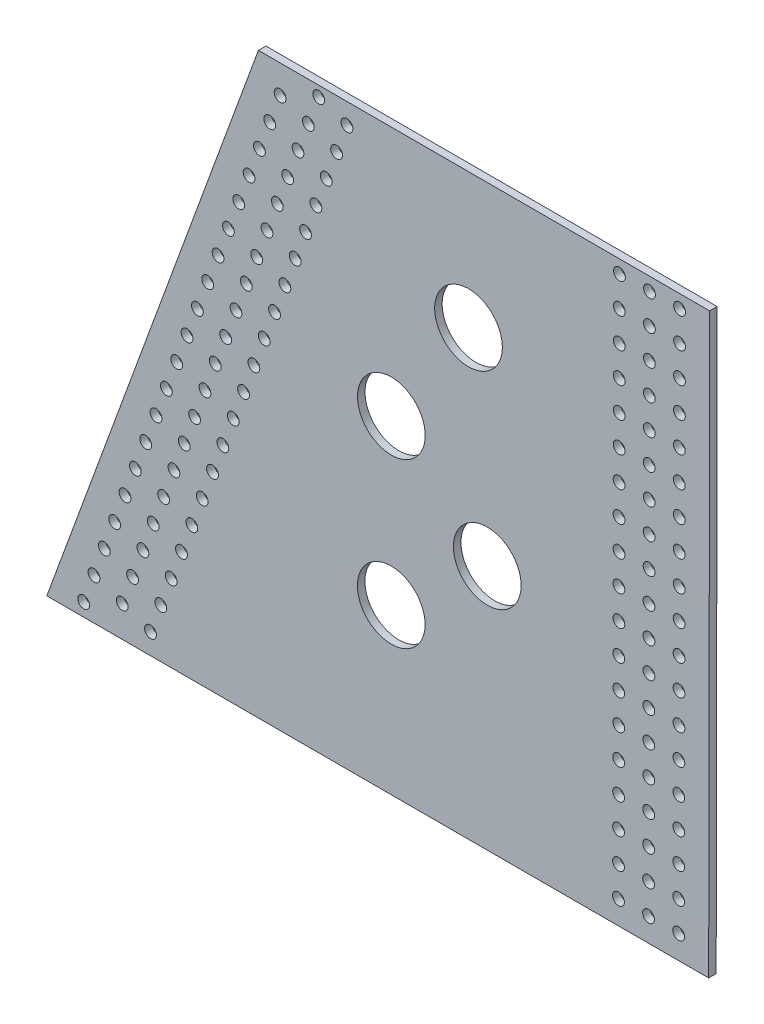
SolidWorks part; units mm, degrees
ref_plane "Front Plane" through (0, 0, 0) normal (0, 0, 1) x (1, 0, 0)
ref_plane "Top Plane" through (0, 0, 0) normal (0, 1, 0) x (1, 0, 0)
ref_plane "Right Plane" through (0, 0, 0) normal (1, 0, 0) x (0, 0, -1)
sketch "Sketch4" plane through (0, 0, 0) normal (0, 0, 1) x (1, 0, 0)
  line B0 (93.7764, 244.0959) -> (284.2764, 244.0959)
  line B1 (284.2764, 244.0959) -> (283.8532, 0)
  line B2 (283.8532, 0) -> (4.4532, 0)
  line B3 (4.4532, 0) -> (93.7764, 244.0959)
  circle B4 centre (182.4682, 187.0319) radius 14.2875
  circle B5 centre (149.9008, 138.4688) radius 14.2875
  circle B6 centre (134.0055, 158.4355) radius 2.4892
  circle B7 centre (165.6949, 118.7313) radius 2.4892
  circle B8 centre (190.3928, 103.8494) radius 14.2875
  circle B9 centre (149.8584, 69.3292) radius 14.2875
  circle B10 centre (197.3682, 18.7438) radius 2.4892
  circle B11 centre (115.0722, 40.7409) radius 9.525
  circle B12 centre (184.6682, 40.7409) radius 9.525
  circle B13 centre (210.0682, 40.7409) radius 2.4892
  circle B14 centre (171.9682, 18.7438) radius 2.4892
  circle B15 centre (159.2682, 40.7409) radius 2.4892
  circle B16 centre (171.9682, 62.7379) radius 2.4892
  circle B17 centre (197.3682, 62.7379) radius 2.4892
  circle B18 centre (140.4722, 40.7409) radius 2.4892
  circle B19 centre (127.7722, 18.7438) radius 2.4892
  circle B20 centre (102.3722, 18.7438) radius 2.4892
  circle B21 centre (89.6722, 40.7409) radius 2.4892
  circle B22 centre (102.3722, 62.7379) radius 2.4892
  circle B23 centre (127.7722, 62.7379) radius 2.4892
sketch_block_instance "Block-Gearbox_Plate1-2"
sketch_block "Block-Gearbox_Plate1" parameters "D3"=28.575, "D4"=4.9784, "D5"=4.9784, "D6"=28.575, "D7"=28.575, "D8"=28.575, "D9"=19.05, "D10"=19.05, "D11"=4.9784, "D14"=4.9784, "D1"=190.5, "D2"=279.4, "D12"=25.4, "D13"=25.4, "D15"=25.4
extrude "Boss-Extrude2" add sketch "Sketch4" along normal blind 3.175 separate body
sketch "Sketch11" plane through (0, 0, 3.175) normal (0, 0, 1) x (1, 0, 0)
  line L0 (231.6101, -832.4231) -> (318.2903, 49167.5018) construction
  line L6 (283.8532, 0) -> (284.2764, 244.0959) construction
  line L7 (284.2764, 244.0959) -> (93.7764, 244.0959) construction
  line L8 (271.5667, 238.5079) -> (258.8667, 238.5079) construction
  line L9 (271.5667, 238.5079) -> (271.5447, 225.8079) construction
  line L10 (4.4532, 0) -> (283.8532, 0) construction
  line L11 (135.8908, 211.3577) -> (-17046.5435, -46743.5564) construction
  line L12 (93.7764, 244.0959) -> (4.4532, 0) construction
  line L13 (93.7764, 244.0959) -> (47048.6904, -16938.3384) construction
  line L14 (102.9315, 232.1579) -> (114.858, 227.7936) construction
  line L15 (102.9315, 232.1579) -> (98.5671, 220.2313) construction
  line L16 (114.858, 227.7936) -> (119.2224, 239.7201) construction
  circle A0 centre (271.5667, 238.5079) radius 2.4892
  circle A1 centre (258.8667, 238.5079) radius 2.4892
  circle A2 centre (246.1667, 238.5079) radius 2.4892
  circle A3 centre (258.8447, 225.8079) radius 2.4892
  circle A4 centre (246.1447, 225.8079) radius 2.4892
  circle A5 centre (258.8227, 213.1079) radius 2.4892
  circle A6 centre (246.1227, 213.1079) radius 2.4892
  circle A7 centre (258.8006, 200.4079) radius 2.4892
  circle A8 centre (246.1006, 200.4079) radius 2.4892
  circle A9 centre (258.7786, 187.708) radius 2.4892
  circle A10 centre (246.0786, 187.708) radius 2.4892
  circle A11 centre (258.7566, 175.008) radius 2.4892
  circle A12 centre (246.0566, 175.008) radius 2.4892
  circle A13 centre (258.7346, 162.308) radius 2.4892
  circle A14 centre (246.0346, 162.308) radius 2.4892
  circle A15 centre (258.7126, 149.608) radius 2.4892
  circle A16 centre (246.0126, 149.608) radius 2.4892
  circle A17 centre (258.6906, 136.908) radius 2.4892
  circle A18 centre (245.9906, 136.908) radius 2.4892
  circle A19 centre (258.6685, 124.2081) radius 2.4892
  circle A20 centre (245.9685, 124.2081) radius 2.4892
  circle A21 centre (258.6465, 111.5081) radius 2.4892
  circle A22 centre (245.9465, 111.5081) radius 2.4892
  circle A23 centre (258.6245, 98.8081) radius 2.4892
  circle A24 centre (245.9245, 98.8081) radius 2.4892
  circle A25 centre (258.6025, 86.1081) radius 2.4892
  circle A26 centre (245.9025, 86.1081) radius 2.4892
  circle A27 centre (258.5805, 73.4081) radius 2.4892
  circle A28 centre (245.8805, 73.4081) radius 2.4892
  circle A29 centre (258.5585, 60.7082) radius 2.4892
  circle A30 centre (245.8585, 60.7082) radius 2.4892
  circle A31 centre (258.5364, 48.0082) radius 2.4892
  circle A32 centre (245.8364, 48.0082) radius 2.4892
  circle A33 centre (258.5144, 35.3082) radius 2.4892
  circle A34 centre (245.8144, 35.3082) radius 2.4892
  circle A35 centre (258.4924, 22.6082) radius 2.4892
  circle A36 centre (245.7924, 22.6082) radius 2.4892
  circle A37 centre (258.4704, 9.9082) radius 2.4892
  circle A38 centre (245.7704, 9.9082) radius 2.4892
  circle A39 centre (271.5447, 225.8079) radius 2.4892
  circle A40 centre (271.5227, 213.1079) radius 2.4892
  circle A41 centre (271.5006, 200.4079) radius 2.4892
  circle A42 centre (271.4786, 187.708) radius 2.4892
  circle A43 centre (271.4566, 175.008) radius 2.4892
  circle A44 centre (271.4346, 162.308) radius 2.4892
  circle A45 centre (271.4126, 149.608) radius 2.4892
  circle A46 centre (271.3906, 136.908) radius 2.4892
  circle A47 centre (271.3685, 124.2081) radius 2.4892
  circle A48 centre (271.3465, 111.5081) radius 2.4892
  circle A49 centre (271.3245, 98.8081) radius 2.4892
  circle A50 centre (271.3025, 86.1081) radius 2.4892
  circle A51 centre (271.2805, 73.4081) radius 2.4892
  circle A52 centre (271.2585, 60.7082) radius 2.4892
  circle A53 centre (271.2364, 48.0082) radius 2.4892
  circle A54 centre (271.2144, 35.3082) radius 2.4892
  circle A55 centre (271.1924, 22.6082) radius 2.4892
  circle A56 centre (271.1704, 9.9082) radius 2.4892
  circle A57 centre (102.9315, 232.1579) radius 2.4892
  circle A58 centre (114.858, 227.7936) radius 2.4892
  circle A59 centre (126.7846, 223.4292) radius 2.4892
  circle A60 centre (110.4937, 215.867) radius 2.4892
  circle A61 centre (122.4202, 211.5027) radius 2.4892
  circle A62 centre (106.1294, 203.9405) radius 2.4892
  circle A63 centre (118.0559, 199.5761) radius 2.4892
  circle A64 centre (101.765, 192.0139) radius 2.4892
  circle A65 centre (113.6916, 187.6496) radius 2.4892
  circle A66 centre (97.4007, 180.0874) radius 2.4892
  circle A67 centre (109.3272, 175.723) radius 2.4892
  circle A68 centre (93.0363, 168.1608) radius 2.4892
  circle A69 centre (104.9629, 163.7965) radius 2.4892
  circle A70 centre (88.672, 156.2343) radius 2.4892
  circle A71 centre (100.5985, 151.8699) radius 2.4892
  circle A72 centre (84.3077, 144.3077) radius 2.4892
  circle A73 centre (96.2342, 139.9434) radius 2.4892
  circle A74 centre (79.9433, 132.3812) radius 2.4892
  circle A75 centre (91.8699, 128.0168) radius 2.4892
  circle A76 centre (75.579, 120.4546) radius 2.4892
  circle A77 centre (87.5055, 116.0903) radius 2.4892
  circle A78 centre (71.2146, 108.5281) radius 2.4892
  circle A79 centre (83.1412, 104.1637) radius 2.4892
  circle A80 centre (66.8503, 96.6015) radius 2.4892
  circle A81 centre (78.7769, 92.2372) radius 2.4892
  circle A82 centre (62.486, 84.675) radius 2.4892
  circle A83 centre (74.4125, 80.3106) radius 2.4892
  circle A84 centre (58.1216, 72.7484) radius 2.4892
  circle A85 centre (70.0482, 68.3841) radius 2.4892
  circle A86 centre (53.7573, 60.8219) radius 2.4892
  circle A87 centre (65.6838, 56.4575) radius 2.4892
  circle A88 centre (49.393, 48.8953) radius 2.4892
  circle A89 centre (61.3195, 44.531) radius 2.4892
  circle A90 centre (45.0286, 36.9688) radius 2.4892
  circle A91 centre (56.9552, 32.6044) radius 2.4892
  circle A92 centre (40.6643, 25.0422) radius 2.4892
  circle A93 centre (52.5908, 20.6779) radius 2.4892
  circle A94 centre (36.2999, 13.1157) radius 2.4892
  circle A95 centre (48.2265, 8.7513) radius 2.4892
  circle A96 centre (31.9356, 1.1891) radius 2.4892 [skipped]
  circle A97 centre (43.8621, -3.1752) radius 2.4892 [skipped]
  circle A98 centre (98.5671, 220.2313) radius 2.4892
  circle A99 centre (94.2028, 208.3048) radius 2.4892
  circle A100 centre (89.8385, 196.3782) radius 2.4892
  circle A101 centre (85.4741, 184.4517) radius 2.4892
  circle A102 centre (81.1098, 172.5252) radius 2.4892
  circle A103 centre (76.7454, 160.5986) radius 2.4892
  circle A104 centre (72.3811, 148.6721) radius 2.4892
  circle A105 centre (68.0168, 136.7455) radius 2.4892
  circle A106 centre (63.6524, 124.819) radius 2.4892
  circle A107 centre (59.2881, 112.8924) radius 2.4892
  circle A108 centre (54.9238, 100.9659) radius 2.4892
  circle A109 centre (50.5594, 89.0393) radius 2.4892
  circle A110 centre (46.1951, 77.1128) radius 2.4892
  circle A111 centre (41.8307, 65.1862) radius 2.4892
  circle A112 centre (37.4664, 53.2597) radius 2.4892
  circle A113 centre (33.1021, 41.3331) radius 2.4892
  circle A114 centre (28.7377, 29.4066) radius 2.4892
  circle A115 centre (24.3734, 17.48) radius 2.4892
  circle A116 centre (20.0091, 5.5535) radius 2.4892
  circle A117 centre (119.2224, 239.7201) radius 2.4892
  circle A118 centre (131.1489, 235.3558) radius 2.4892
  dimension "D4" = 4.9784
  dimension "D11" = 4.9784
  dimension "D1" = 50.8
  dimension "D2" = 5.588
  dimension "D3" = 12.7
  dimension "D7" = 12.7
  dimension "D8" = 12.7
  dimension "D9" = 9.9082
  dimension "D10" = 50.8
  dimension "D12" = 11.938
  dimension "D13" = 12.7
  dimension "D16" = 12.7
  dimension "D17" = 12.7
  dimension "D18" = 5.5535
  dimension "D20" = 12.7
  dimension "D5" = 3
  dimension "D6" = 19
  dimension "D14" = 3
  dimension "D15" = 20
  dimension "D19" = 2
extrude "Cut-Extrude2" cut sketch "Sketch11" against normal blind 3.175
sketch "Sketch12" plane through (0, 0, 3.175) normal (0, 0, 1) x (1, 0, 0)
  circle A0 centre (134.0055, 158.4355) radius 2.4892
  circle A1 centre (165.6949, 118.7313) radius 2.4892
  circle A2 centre (184.6682, 40.7409) radius 29.21
  circle A3 centre (115.0722, 40.7409) radius 29.21
  circle A4 centre (165.6949, 118.7313) radius 2.4892 construction
  dimension "D1" = 4.9784
  dimension "D2" = 4.9784
  dimension "D3" = 58.42
  dimension "D4" = 58.42
extrude "Boss-Extrude3" add sketch "Sketch12" against normal blind 3.175
